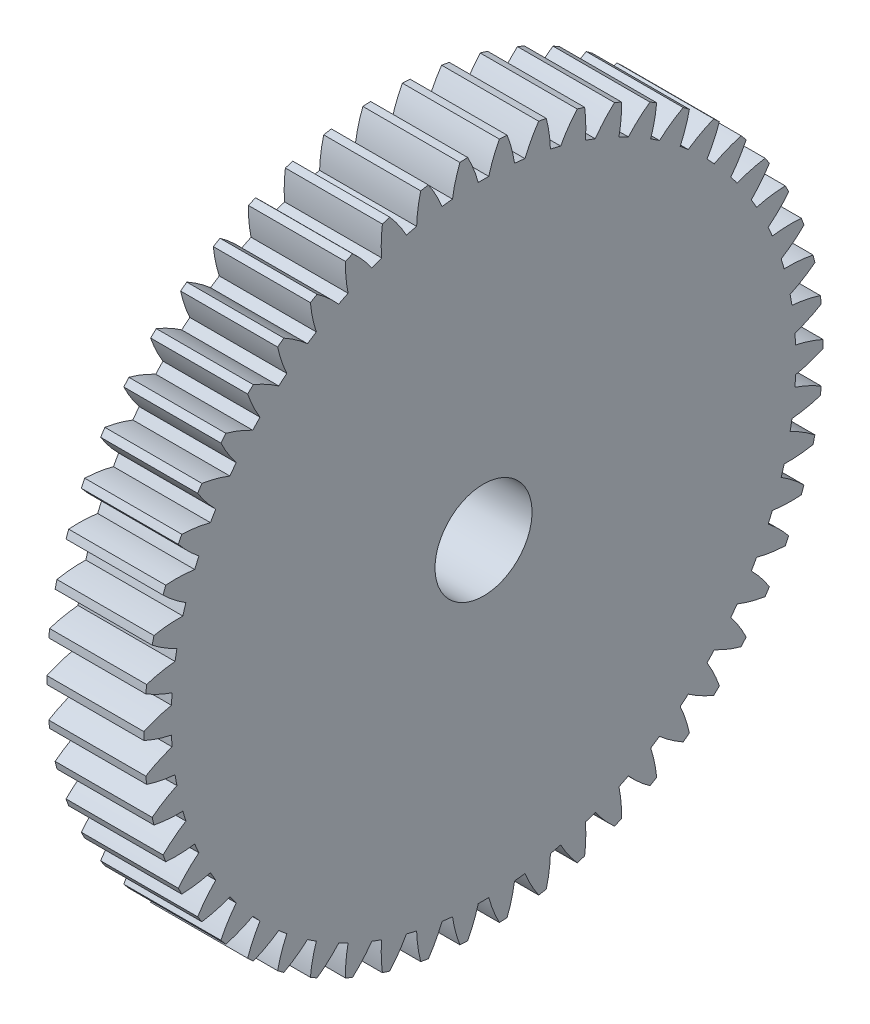
SolidWorks part; units mm, degrees
ref_plane "Plane1" through (0, 0, 0) normal (0, 0, 1) x (1, 0, 0)
ref_plane "Plane2" through (0, 0, 0) normal (0, 1, 0) x (1, 0, 0)
ref_plane "Plane3" through (0, 0, 0) normal (1, 0, 0) x (0, 0, -1)
other "Configuration Table"
sketch "HoldingSke" plane through (0, 0, 0) normal (0, 1, 0) x (1, 0, 0)
  line L0 (0, 0) -> (0.5878, -0.809)
  line L1 (-15, 0) -> (100, 0) construction
  line L2 (0, 0) -> (-2.1039, 2.3779)
  line L3 (0, 0) -> (-11.863, 4.5341)
  line L4 (0, 0) -> (5.0761, 6.9867)
  line L5 (0, 0) -> (-46.8476, -17.4728)
  line L6 (0, 0) -> (-6.6317, -4.4744)
  line L7 (-2.1039, 2.3779) -> (8.6586, 51.2059)
  line L8 (-76.2, 54.61) -> (-74.8, 54.61)
  line L9 (-71.009, 38.7566) -> (-53.1078, 45.2721)
  line L10 (-76.2, 71.12) -> (104.1128, 71.12)
  line L11 (0, 0) -> (-8, 0)
  line L12 (-76.2, 101.6) -> (-76.162, 101.6)
  line L13 (24.9733, 27.94) -> (52.9518, 28.4284)
  line L14 (24.9733, 27.94) -> (24.9743, 27.94)
  line L15 (24.9733, 27.94) -> (100.4006, 29.5858)
  line L16 (-63.627, -1) -> (-12.827, -1)
  circle A0 centre (0, 0) radius 4
  circle A1 centre (0, 0) radius 25.749
  circle A2 centre (0, 0) radius 37.5
  circle A3 centre (0, 0) radius 4
  dimension "MHD" = 51.498
  dimension "Hub_dia" = 75
  dimension "Bore" = 8
  dimension "MBD" = 8
  dimension "Num_teeth" = 54
  dimension "Pitch" = 1
  dimension "Overall_len" = 50
  dimension "Show_teeth" = 54
  dimension "Thickness" = 8
  dimension "OAL" = 50.0001
  dimension "T_dim" = 1.4
  dimension "Ap" = 20
  dimension "H" = 19.05
  dimension "Pitch_radius" = 180.3128
  dimension "Width" = 8
  dimension "Backlash" = 0.038
  dimension "Addendum_fac" = 1
  dimension "Dedendum_fac" = 1.25
  dimension "Clearance_fac" = 0.25
  dimension "Dedendum_add" = 0.001
  dimension "Module" = 1
sketch "BasProSke" plane through (0, 0, 0) normal (0, 1, 0) x (1, 0, 0)
  line L0 (-10, 0) -> (60, 0) construction
  line L1 (0, 0) -> (0, 28)
  line L2 (0, 0) -> (8, 0)
  line L3 (8, 0) -> (8, 28)
  line L4 (8, 28) -> (0, 28)
  dimension "Thickness" = 8
  dimension "Diameter" = 56
revolve "Base-Revolve" add sketch "BasProSke" angle 360 about L0
sketch "TooCutSke" plane through (0, 0, 0) normal (1, 0, 0) x (0, 0, -1)
  line L1 (0, 0) -> (0, 107) construction
  line L2 (0, 0) -> (-0.8518, 26.9866) construction
  line L3 (0, 0) -> (-3.1387, 53.8895) construction
  line L4 (-0.8518, 26.9866) -> (-1.5694, 26.9448) construction
  arc A0 (0.4343, 25.7453) -> (-0.4343, 25.7453) centre (0, 0) ccw
  arc A1 (1.322, 27.9942) -> (-1.322, 27.9942) centre (0, 0) ccw
  circle A2 centre (0, 0) radius 27 construction
  circle A3 centre (0, 0) radius 25.3717 construction
  arc A4 (-0.4343, 25.7453) -> (-1.322, 27.9942) centre (-10.8608, 22.9296) ccw
  arc A5 (1.322, 27.9942) -> (0.4343, 25.7453) centre (10.8608, 22.9296) ccw
  dimension "Root_dia" = 51.498
  dimension "Overcut_dia" = 56.0508
  dimension "Pitch_dia" = 54
  dimension "Base_dia" = 50.7434
  dimension "Flank_rad" = 10.8
  dimension "Half_ang" = 3.333
  dimension "Half_CT" = 0.7188
extrude "ToothCut" cut sketch "TooCutSke" along normal through all
fillet "Breaks" [suppressed] radius 0.02
fillet "RootFillets" [suppressed] radius 0.251
pattern_circular "TeethCuts" count 54 every 6.667 about axis through (-10, 0, 0) along (1, 0, 0) of "ToothCut", "RootFillets", "Breaks"
sketch "HubNeaOneSke" plane through (0, 0, 0) normal (-1, 0, 0) x (0, 0, 1)
  circle A0 centre (0, 0) radius 25.749
  dimension "Diameter" = 51.498
extrude "HubNearOne" [suppressed] add sketch "HubNeaOneSke" along normal blind 42.0001
sketch "HubNeaBotSke" plane through (0, 0, 0) normal (-1, 0, 0) x (0, 0, 1)
  circle A0 centre (0, 0) radius 25.749
  dimension "Diameter" = 51.498
extrude "HubNearBoth" [suppressed] add sketch "HubNeaBotSke" along normal blind 21
ref_plane "FarPln" through (8, 0, 0) normal (1, 0, 0) x (0, 0, -1)
sketch "HubFarSke" plane through (8, 0, 0) normal (1, 0, 0) x (0, 0, -1)
  circle A0 centre (0, 0) radius 25.749
  dimension "Diameter" = 51.498
extrude "HubFar" [suppressed] add sketch "HubFarSke" along normal blind 21
sketch "BorSke" plane through (0, 0, 0) normal (1, 0, 0) x (0, 0, -1)
  circle A0 centre (0, 0) radius 4
  dimension "Diameter" = 8
extrude "Bore" cut sketch "BorSke" along normal mid plane 100.0001
sketch "KeySke" plane through (0, 0, 0) normal (1, 0, 0) x (0, 0, -1)
  line L0 (-1.5, 0) -> (-1.5, 5.4)
  line L1 (-1.5, 5.4) -> (1.5, 5.4)
  line L2 (1.5, 5.4) -> (1.5, 0)
  line L3 (0, 0) -> (0, 34) construction
  line L4 (-1.5, 0) -> (1.5, 0)
  dimension "Offset" = 5.4
  dimension "Width" = 3
extrude "Keyway" [suppressed] cut sketch "KeySke" along normal mid plane 100.0001
pattern_circular "Keyway2" [suppressed] count 2 every 90 about axis through (-10, 0, 0) along (1, 0, 0)
equation "' \"Module@HoldingSke\" = 6.35"
equation "' \"Num_teeth@HoldingSke\" = 12"
equation "' \"Ap@HoldingSke\" =  20"
equation "' \"Ap@HoldingSke\" = 20"
equation "' \"Width@HoldingSke\" = 0.5 * 25.4"
equation "' \"Hub_dia@HoldingSke\"= 1 * 25.4"
equation "' \"Hub_dia@HoldingSke\" = 1 * 25.4"
equation "' \"Overall_len@HoldingSke\" = 1.0 * 25.4"
equation "' \"Bore@HoldingSke\" = 0.75 * 25.4"
equation "' \"T_dim@HoldingSke\" = 0.1 * 25.4"
equation "' \"Width@KeySke\" = 0.25 * 25.4"
equation "' \"Show_teeth@HoldingSke\" = 13"
equation "' \"Backlash@HoldingSke\" = 0.009 * 25.4"
equation "' \"Addendum_fac@HoldingSke\" = 1.0"
equation "' \"Dedendum_fac@HoldingSke\" = 1.25"
equation "' \"Dedendum_add@HoldingSke\" = 0.00005 * 25.4"
equation "' \"Clearance_fac@HoldingSke\" = 0.25"
equation "\"Pitch@HoldingSke\" = 1 / \"Module@HoldingSke\""
equation "\"Overcut_dia@TooCutSke\" = (\"Num_teeth@HoldingSke\" + 2 * \"Addendum_fac@HoldingSke\") / \"Pitch@HoldingSke\" + 0.002 * 25.4"
equation "\"Pitch_dia@TooCutSke\" = \"Num_teeth@HoldingSke\" / \"Pitch@HoldingSke\""
equation "\"Base_dia@TooCutSke\" = \"Num_teeth@HoldingSke\" / \"Pitch@HoldingSke\" * cos((\"Ap@HoldingSke\"  * 3.14159265 / 180))"
equation "\"Root_dia@TooCutSke\" = (\"Num_teeth@HoldingSke\" + 2) / \"Pitch@HoldingSke\" - 2 * (\"Addendum_fac@HoldingSke\" + \"Dedendum_fac@HoldingSke\") / \"Pitch@HoldingSke\" - \"Dedendum_add@HoldingSke\" * 2"
equation "\"Half_ang@TooCutSke\" = 180 / \"Num_teeth@HoldingSke\""
equation "\"Half_CT@TooCutSke\" = \"Num_teeth@HoldingSke\" / \"Pitch@HoldingSke\" * sin((3.14159265 / 2 / \"Num_teeth@HoldingSke\")) / 2 - 7 * \"Backlash@HoldingSke\" / 4"
equation "\"Flank_rad@TooCutSke\" = \"Num_teeth@HoldingSke\" / \"Pitch@HoldingSke\" / 5"
equation "\"Radius@RootFillets\" = \"Clearance_fac@HoldingSke\" / \"Pitch@HoldingSke\" + \"Dedendum_add@HoldingSke\""
equation "\"Break_rad@Breaks\" = 0.02 / \"Pitch@HoldingSke\""
equation "\"Thickness@HoldingSke\" = \"Width@HoldingSke\""
equation "\"OAL@HoldingSke\" = \"Thickness@HoldingSke\""
equation "\"MHD@HoldingSke\" = (\"Num_teeth@HoldingSke\" + 2) / \"Pitch@HoldingSke\" - 2 * (\"Addendum_fac@HoldingSke\" + \"Dedendum_fac@HoldingSke\")  / \"Pitch@HoldingSke\" - \"Dedendum_add@HoldingSke\" * 2"
equation "\"MBD@HoldingSke\" = (\"Num_teeth@HoldingSke\" + 2) / \"Pitch@HoldingSke\" - 2 * (\"Addendum_fac@HoldingSke\" + \"Dedendum_fac@HoldingSke\")  / \"Pitch@HoldingSke\" - \"Dedendum_add@HoldingSke\" * 2 - 0.002 * 25.4"
equation "\"MHD@HoldingSke\" = ((sgn( \"MHD@HoldingSke\" - \"Hub_dia@HoldingSke\" )-1)*( \"MHD@HoldingSke\" - \"Hub_dia@HoldingSke\" ))/-2+ \"Hub_dia@HoldingSke\""
equation "\"MBD@HoldingSke\" = ((sgn( \"MBD@HoldingSke\" - \"Bore@HoldingSke\" )-1)*( \"MBD@HoldingSke\" - \"Bore@HoldingSke\" ))/-2+ \"Bore@HoldingSke\""
equation "\"OAL@HoldingSke\" = ((sgn( \"OAL@HoldingSke\" - \"Overall_len@HoldingSke\" )+1)*( \"OAL@HoldingSke\" - \"Overall_len@HoldingSke\" ))/2 + \"Overall_len@HoldingSke\" + 0.000002 * 25.4"
equation "\"Num_teeth@TeethCuts\" = int( \"Show_teeth@HoldingSke\" ) + 1"
equation "\"Num_teeth@TeethCuts\" = ((sgn( \"Num_teeth@TeethCuts\" - \"Num_teeth@HoldingSke\" )-1)*( \"Num_teeth@TeethCuts\" - \"Num_teeth@HoldingSke\" ))/-2+ \"Num_teeth@HoldingSke\""
equation "\"Num_teeth@TeethCuts\" = ((sgn( \"Num_teeth@TeethCuts\" - 2.0)+1)*( \"Num_teeth@TeethCuts\" - 2.0))/2 +2.0"
equation "\"Angle@TeethCuts\" = 360.0 / \"Num_teeth@HoldingSke\""
equation "\"Diameter@BasProSke\" = (\"Num_teeth@HoldingSke\" + 2 * \"Addendum_fac@HoldingSke\") / \"Pitch@HoldingSke\""
equation "\"Thickness@BasProSke\"  = \"Thickness@HoldingSke\""
equation "' \"Fillet_rad@BasProSke\" =  \"Thickness@HoldingSke\" * 0.05"
equation "' \"Fillet_rad@BasProSke\" = \"Thickness@HoldingSke\" * 0.05"
equation "\"MHD@HoldingSke\" = ((sgn( \"MHD@HoldingSke\" - \"Root_dia@TooCutSke\" )-1)*( \"MHD@HoldingSke\" - \"Root_dia@TooCutSke\" ))/-2+ \"Root_dia@TooCutSke\""
equation "\"Diameter@HubNeaOneSke\" = \"MHD@HoldingSke\""
equation "\"Length@HubNearOne\" = \"OAL@HoldingSke\" - \"Thickness@BasProSke\""
equation "\"Diameter@HubNeaBotSke\" = \"MHD@HoldingSke\""
equation "\"Length@HubNearBoth\" = ( \"OAL@HoldingSke\" - \"Thickness@BasProSke\" ) / 2.0"
equation "\"Thickness@FarPln\" = \"Thickness@BasProSke\""
equation "\"Diameter@HubFarSke\" = \"MHD@HoldingSke\""
equation "\"Length@HubFar\" = ( \"OAL@HoldingSke\" - \"Thickness@BasProSke\" ) / 2.0"
equation "\"Diameter@BorSke\" = \"MBD@HoldingSke\""
equation "\"D1@Bore\" = \"OAL@HoldingSke\" * 2.0"
equation "\"D1@Keyway\" = \"OAL@HoldingSke\" * 2.0"
equation "\"Offset@KeySke\" = \"T_dim@HoldingSke\" + \"MBD@HoldingSke\" / 2.0"
